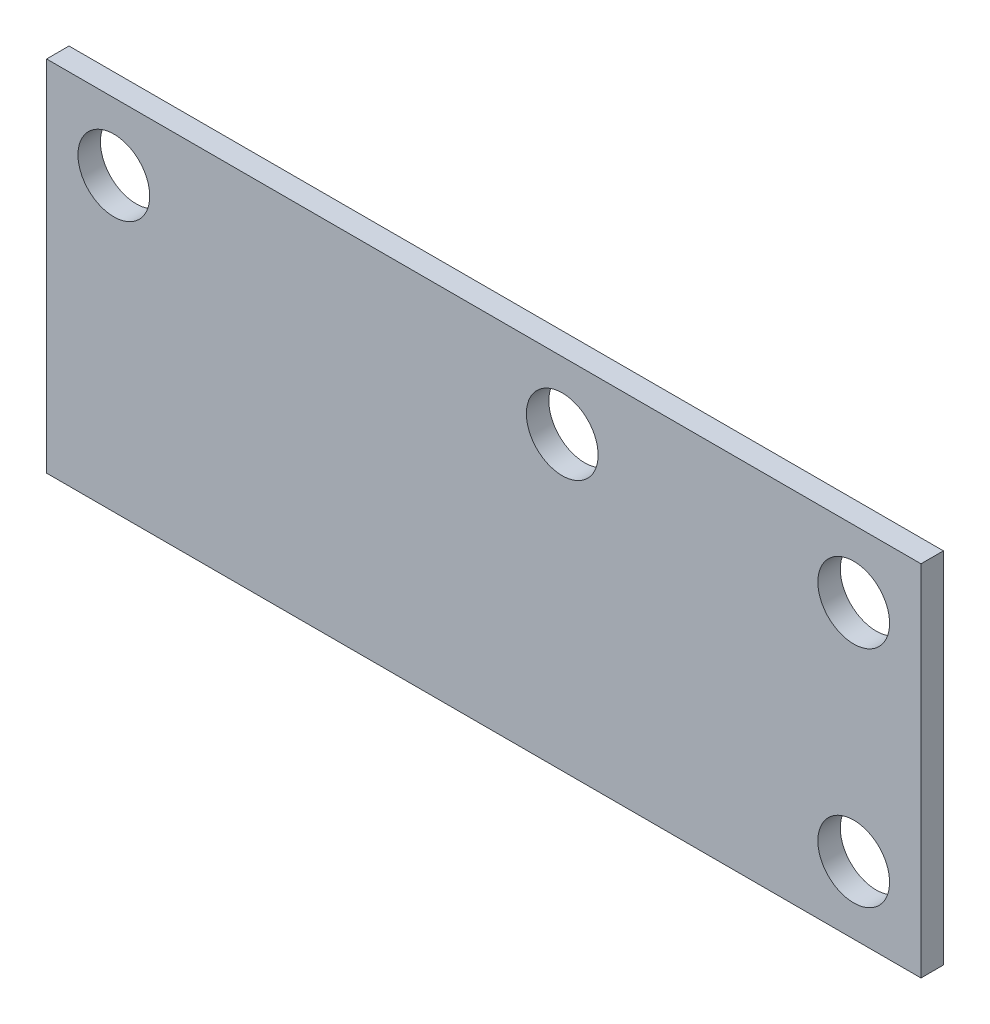
SolidWorks part; units mm, degrees
ref_plane "Plan de face" through (0, 0, 0) normal (0, 0, 1) x (1, 0, 0)
ref_plane "Plan de dessus" through (0, 0, 0) normal (0, 1, 0) x (1, 0, 0)
ref_plane "Plan de droite" through (0, 0, 0) normal (1, 0, 0) x (0, 0, -1)
sketch "Esquisse1" plane through (0, 0, 0) normal (0, 0, 1) x (1, 0, 0)
  line L1 (0, 0) -> (39, 0)
  line L2 (0, 0) -> (0, 16)
  line L3 (0, 16) -> (39, 16)
  line L4 (39, 0) -> (39, 16)
  dimension "D1" = 16
  dimension "D2" = 39
extrude "Boss.-Extru.1" add sketch "Esquisse1" along normal blind 1
sketch "Esquisse2" plane through (0, 0, 0) normal (0, 0, -1) x (-1, 0, 0)
  line L0 (-39, 16) -> (0, 16) construction
  line L1 (0, 16) -> (0, 0) construction
  line L2 (-39, 0) -> (-39, 16) construction
  line L3 (0, 0) -> (-39, 0) construction
  circle A0 centre (-36, 13) radius 1.6
  circle A1 centre (-36, 3) radius 1.6
  circle A2 centre (-23, 13) radius 1.6
  circle A3 centre (-3, 13) radius 1.6
  dimension "D1" = 3.2
  dimension "D2" = 3.2
  dimension "D3" = 3.2
  dimension "D4" = 3.2
  dimension "D5" = 3
  dimension "D6" = 3
  dimension "D7" = 3
  dimension "D8" = 3
  dimension "D9" = 3
  dimension "D10" = 3
  dimension "D11" = 3
  dimension "D12" = 20
extrude "Enlèv. mat.-Extru.1" cut sketch "Esquisse2" against normal blind 1
